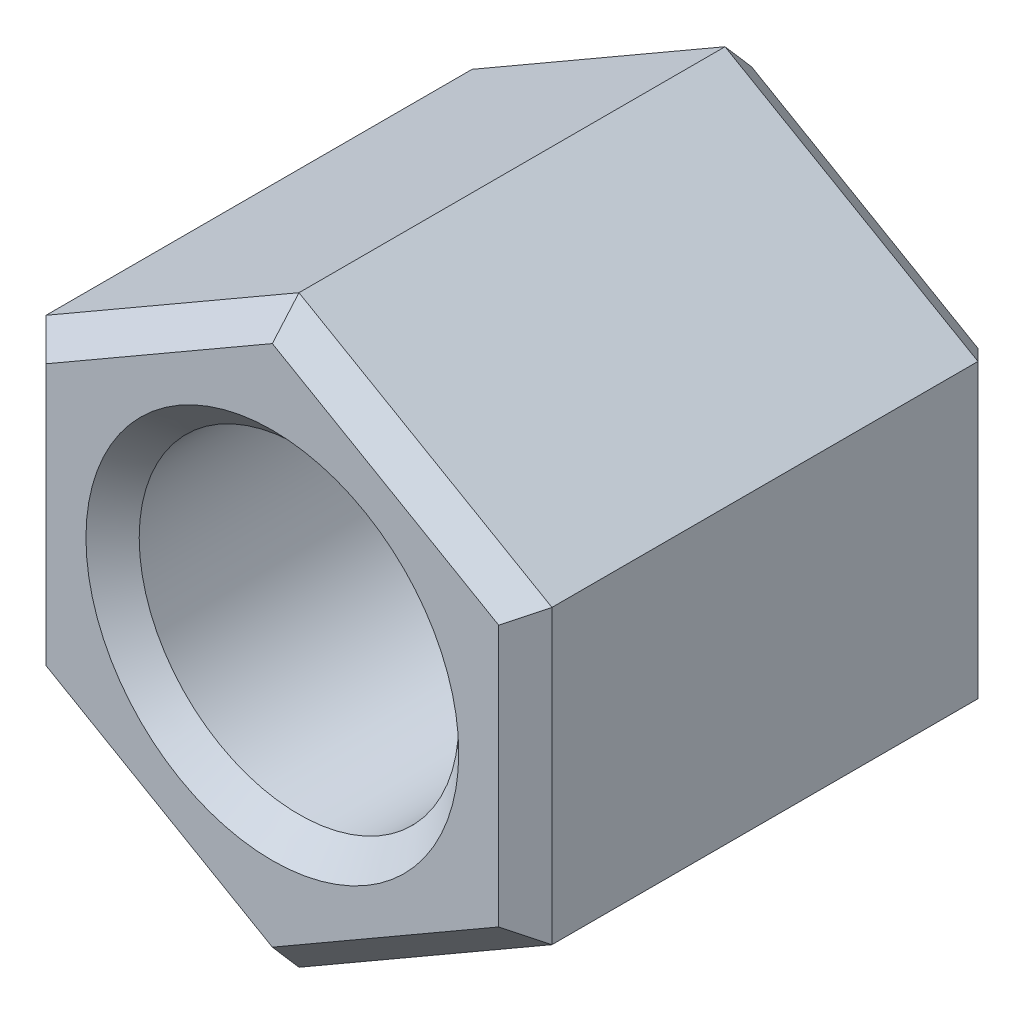
SolidWorks part; units mm, degrees
ref_plane "Plan de face" through (0, 0, 0) normal (0, 0, 1) x (1, 0, 0)
ref_plane "Plan de dessus" through (0, 0, 0) normal (0, 1, 0) x (1, 0, 0)
ref_plane "Plan de droite" through (0, 0, 0) normal (1, 0, 0) x (0, 0, -1)
sketch "Esquisse1" plane through (0, 0, 0) normal (0, 0, 1) x (1, 0, 0)
  line L0 (0, 0) -> (0, 10.9697) construction
  line L1 (0, 0) -> (9.5, 0) construction
  line L2 (9.5, -5.4848) -> (9.5, 5.4848)
  line L3 (9.5, 5.4848) -> (0, 10.9697)
  line L4 (9.5, -5.4848) -> (0, -10.9697)
  line L5 (-9.5, -5.4848) -> (0, -10.9697)
  line L6 (-9.5, 5.4848) -> (0, 10.9697)
  line L7 (-9.5, -5.4848) -> (-9.5, 5.4848)
  circle A0 centre (0, 0) radius 6
  dimension "D3" = 12
  dimension "D1" = 120
  dimension "D2" = 19
extrude "Boss.-Extru.1" add sketch "Esquisse1" along normal blind 18
chamfer "Chanfrein1" distance 1 angle 45 14 edges at (6, 0, 0) (-9.5, 0, 0) (-4.75, -8.2272, 0) (4.75, -8.2272, 0) (9.5, 0, 0) (4.75, 8.2272, 0) (-4.75, 8.2272, 0) (6, 0, 18) (4.75, 8.2272, 18) (9.5, 0, 18) (4.75, -8.2272, 18) (-4.75, -8.2272, 18) (-9.5, 0, 18) (-4.75, 8.2272, 18)
